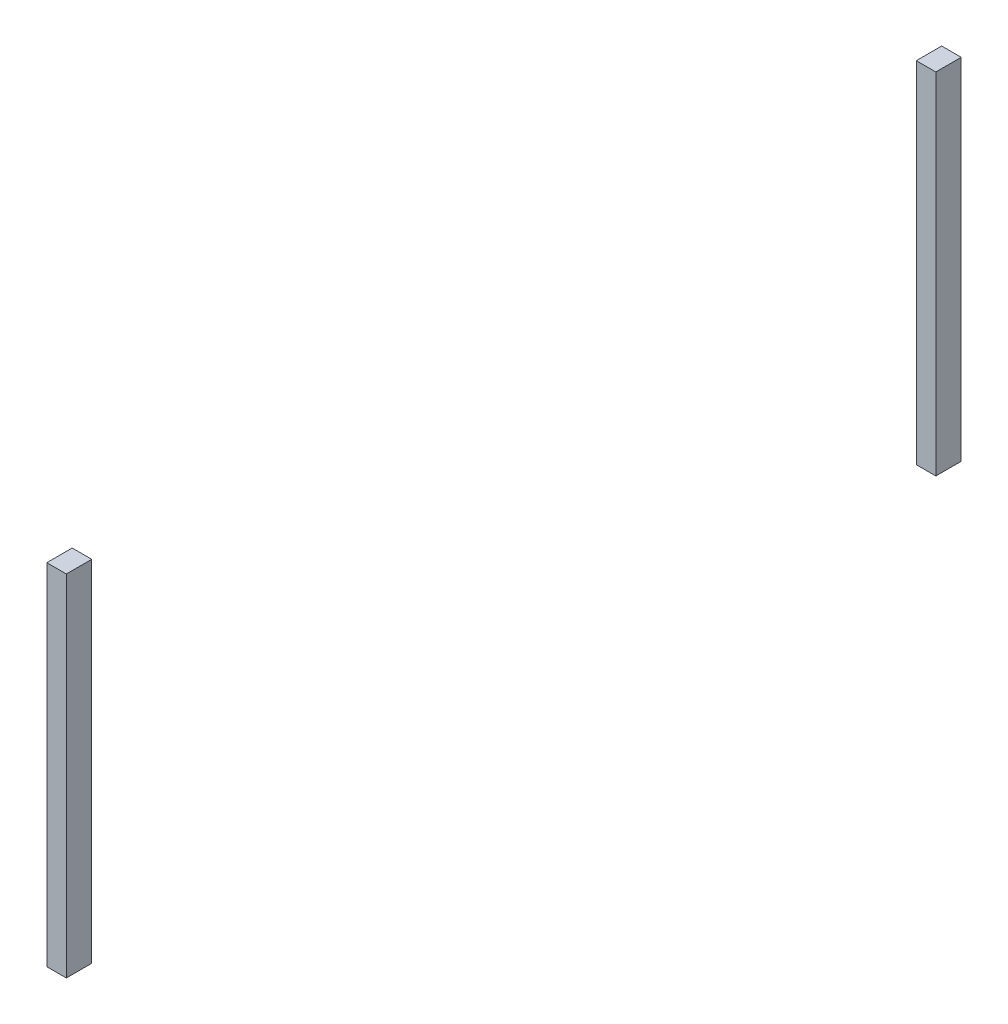
SolidWorks part; units mm, degrees
ref_plane "Front Plane" through (0, 0, 0) normal (0, 0, 1) x (1, 0, 0)
ref_plane "Top Plane" through (0, 0, 0) normal (0, 1, 0) x (1, 0, 0)
ref_plane "Right Plane" through (0, 0, 0) normal (1, 0, 0) x (0, 0, -1)
ref_plane "Plane2" through (256.75, 0, 0) normal (-1, 0, 0) x (0, 0, 1)
sketch "Sketch5" plane through (256.75, 0, 0) normal (-1, 0, 0) x (0, 0, 1)
  line L0 (1970.8, 151) -> (1930.8, 151)
  line L1 (1930.8, 151) -> (1930.8, -400)
  line L2 (1930.8, -400) -> (1970.8, -400)
  line L3 (1970.8, -400) -> (1970.8, 151)
  dimension "D1" = 40
  dimension "D2" = 551
extrude "Boss-Extrude2" add sketch "Sketch5" against normal blind 30.8 separate body
sketch "Sketch10" plane through (256.75, 0, 0) normal (-1, 0, 0) x (0, 0, 1)
  line L0 (561.6, 151) -> (561.6, -400)
  line L1 (561.6, -400) -> (601.6, -400)
  line L2 (601.6, -400) -> (601.6, 151)
  line L3 (601.6, 151) -> (561.6, 151)
  line L4 (1970.8, -400) -> (1970.8, 151) construction
  dimension "D1" = 40
  dimension "D2" = 1409.2
  dimension "D3" = 551
extrude "Boss-Extrude3" add sketch "Sketch10" against normal blind 30.8 separate body
